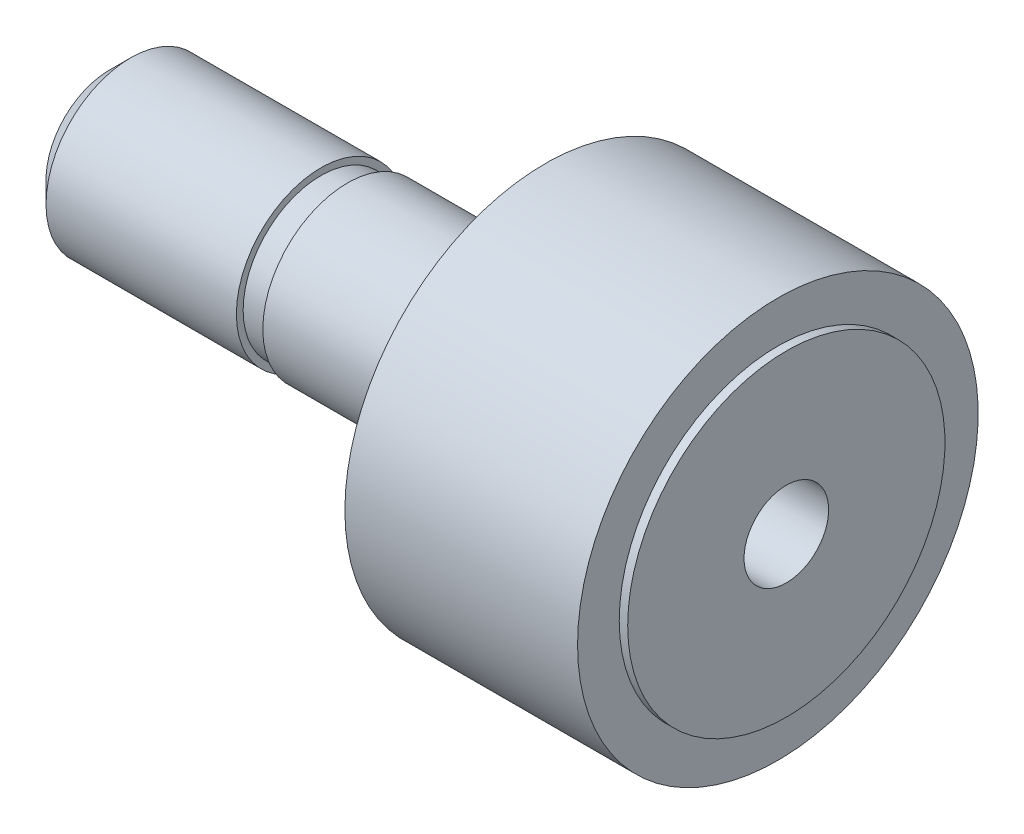
SolidWorks part; units mm, degrees
ref_plane "Piano frontale" through (0, 0, 0) normal (0, 0, 1) x (1, 0, 0)
ref_plane "Piano superiore" through (0, 0, 0) normal (0, 1, 0) x (1, 0, 0)
ref_plane "Piano destro" through (0, 0, 0) normal (1, 0, 0) x (0, 0, -1)
sketch "Schizzo1" plane through (0, 0, 0) normal (0, 0, 1) x (1, 0, 0)
  line L0 (15.9384, 0) -> (15.9384, 2)
  line L1 (15.9384, 2) -> (20.8384, 2)
  line L2 (20.8384, 2) -> (20.8384, 7.5)
  line L3 (20.8384, 7.5) -> (20.4384, 7.5)
  line L4 (20.4384, 7.5) -> (20.4384, 9.47)
  line L5 (20.4384, 9.47) -> (9.4384, 9.47)
  line L6 (9.4384, 9.47) -> (9.4384, 7.5)
  line L7 (9.4384, 7.5) -> (8.8384, 7.5)
  line L8 (8.8384, 7.5) -> (8.8384, 4)
  line L9 (8.8384, 4) -> (0.0884, 4)
  line L10 (0.0884, 4) -> (0.0884, 3.68)
  line L11 (0.0884, 3.68) -> (-1.1616, 3.68)
  line L12 (-1.1616, 3.68) -> (-1.1616, 4)
  line L13 (-1.1616, 4) -> (-11.1616, 4)
  line L14 (-11.1616, 4) -> (-11.1616, 0)
  line L15 (-12.4659, 0) -> (4.6297, 0) construction
  line L16 (-11.1616, 0) -> (15.9384, 0)
  point P14 (20.6384, 7.5)
  dimension "D1" = 0.4
  dimension "D2" = 0.6
  dimension "D3" = 11
  dimension "D4" = 8.75
  dimension "D5" = 1.25
  dimension "D6" = 10
  dimension "D7" = 4.9
  dimension "D8" = 2
  dimension "D9" = 7.5
  dimension "D10" = 9.47
  dimension "D11" = 7.5
  dimension "D12" = 4
  dimension "D13" = 3.68
  dimension "D14" = 4
revolve "Rivoluzione1" add sketch "Schizzo1" angle 360 about L15
chamfer "Smusso1" distance 1 angle 45 1 edges at (-11.1616, 0, 4)
ref_point "Punto1"
